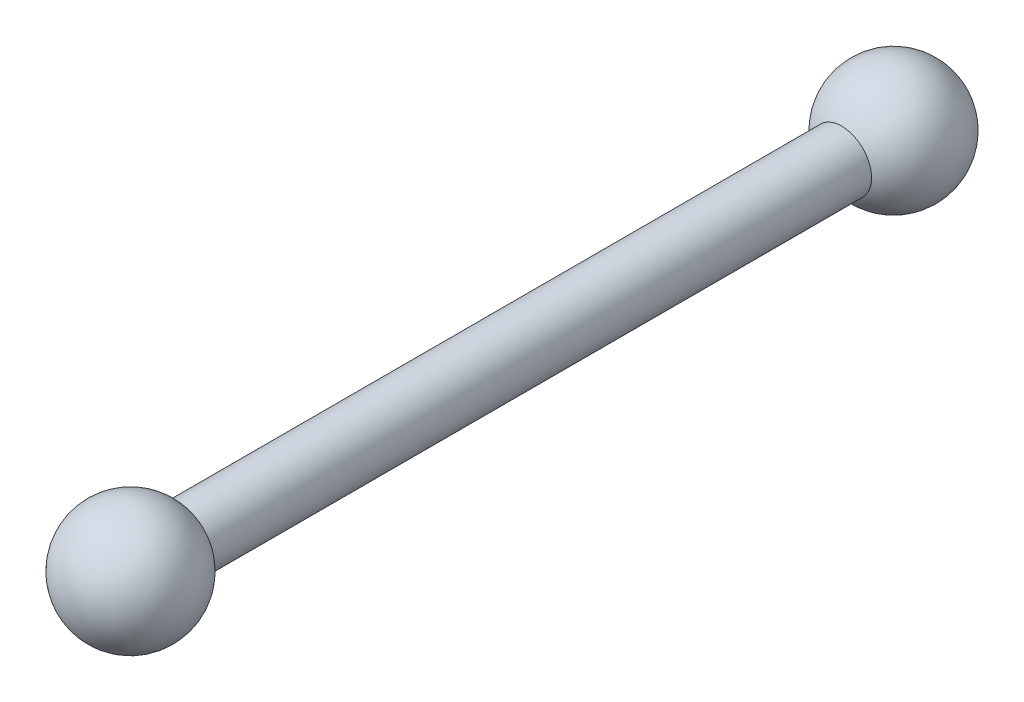
SolidWorks part; units mm, degrees
ref_plane "Front Plane" through (0, 0, 0) normal (0, 0, 1) x (1, 0, 0)
ref_plane "Top Plane" through (0, 0, 0) normal (0, 1, 0) x (1, 0, 0)
ref_plane "Right Plane" through (0, 0, 0) normal (1, 0, 0) x (0, 0, -1)
sketch "Sketch1" plane through (0, 0, 0) normal (0, 0, 1) x (1, 0, 0)
  circle A0 centre (0, 0) radius 2
  dimension "D1" = 4
extrude "Boss-Extrude1" add sketch "Sketch1" against normal blind 45
ref_plane "Plane1" through (0, 0, 3) normal (0, 0, 1) x (1, 0, 0)
sketch "Sketch2" plane through (0, 0, 3) normal (0, 0, 1) x (1, 0, 0)
  line L0 (0, 4) -> (0, -4) construction
  line L1 (0, 4) -> (0, -4)
  arc A1 (0, -4) -> (0, 4) centre (0, 0) ccw
  dimension "D1" = 8
revolve "Revolve1" add sketch "Sketch2" angle 360 about L0
ref_plane "Plane2" through (0, 0, -22.5) normal (0, 0, 1) x (1, 0, 0)
mirror "Mirror2" about plane through (0, 0, -22.5) normal (0, 0, 1) of "Revolve1"
